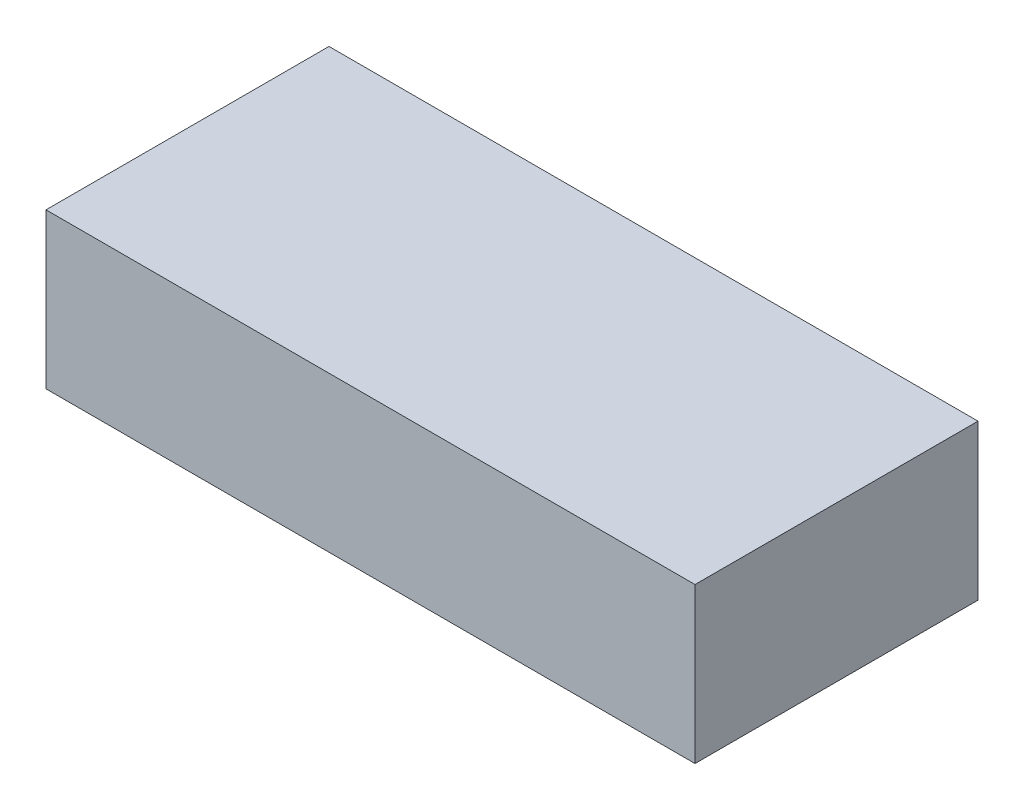
SolidWorks part; units mm, degrees
ref_plane "Front Plane" through (0, 0, 0) normal (0, 0, 1) x (1, 0, 0)
ref_plane "Top Plane" through (0, 0, 0) normal (0, 1, 0) x (1, 0, 0)
ref_plane "Right Plane" through (0, 0, 0) normal (1, 0, 0) x (0, 0, -1)
sketch "Sketch1" plane through (0, 0, 0) normal (0, 1, 0) x (1, 0, 0)
  line L1 (-48.641, 21.209) -> (48.641, 21.209)
  line L2 (-48.641, 21.209) -> (-48.641, -21.209)
  line L3 (-48.641, -21.209) -> (48.641, -21.209)
  line L4 (48.641, 21.209) -> (48.641, -21.209)
  line L5 (-48.641, 21.209) -> (48.641, -21.209) construction
  line L6 (-48.641, -21.209) -> (48.641, 21.209) construction
  point P0 (0, 0)
  dimension "D1" = 97.282
  dimension "D2" = 42.418
extrude "Boss-Extrude1" add sketch "Sketch1" along normal blind 23.241
